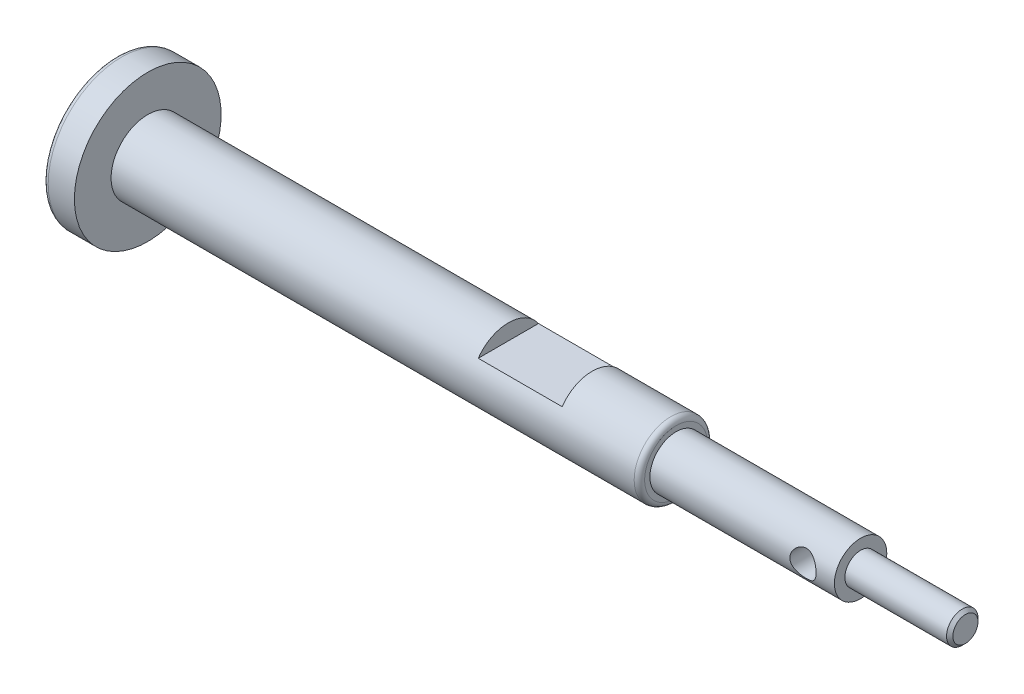
SolidWorks part; units mm, degrees
ref_plane "前视基准面" through (0, 0, 0) normal (0, 0, 1) x (1, 0, 0)
ref_plane "上视基准面" through (0, 0, 0) normal (0, 1, 0) x (1, 0, 0)
ref_plane "右视基准面" through (0, 0, 0) normal (1, 0, 0) x (0, 0, -1)
sketch "草图1" plane through (0, 0, 0) normal (1, 0, 0) x (0, 0, -1)
  circle A0 centre (0, 0) radius 3.5
  dimension "D1" = 7
extrude "凸台-拉伸1" add sketch "草图1" along normal blind 90
sketch "草图2" plane through (0, 0, 0) normal (-1, 0, 0) x (0, 0, 1)
  circle A0 centre (0, 0) radius 7
  dimension "D1" = 14
extrude "凸台-拉伸2" add sketch "草图2" along normal blind 3
fillet "圆角1" radius 0.5 1 edges at (-3, 0, 7)
sketch "草图3" plane through (0, 0, 0) normal (0, 0, 1) x (1, 0, 0)
  line L0 (0, 0) -> (33.4, 0) construction
  line L1 (33.4, 0) -> (34.4, 0) construction
  line L2 (34.4, 0) -> (34.4, 3.5) construction
  line L3 (90, 3.5) -> (0, 3.5) construction
  line L5 (42.4, 2) -> (34.4, 2)
  line L6 (42.4, 2) -> (42.4, 3.5)
  line L7 (42.4, 3.5) -> (34.4, 3.5)
  line L8 (34.4, 2) -> (34.4, 3.5)
  line L9 (42.4, 2) -> (34.4, 3.5) construction
  line L10 (42.4, 3.5) -> (34.4, 2) construction
  point P4 (38.4, 2.75)
  dimension "D1" = 33.4
  dimension "D2" = 1
  dimension "D3" = 1.5
  dimension "D4" = 8
extrude "切除-拉伸1" cut sketch "草图3" against normal through all both and the other way through all
sketch "草图4" plane through (0, 0, 0) normal (0, 0, 1) x (1, 0, 0)
  line L0 (34.4, 0) -> (50.4, 0) construction
  line L1 (50.4, 0) -> (50.4, 3.5) construction
  line L2 (90, 3.5) -> (42.4, 3.5) construction
  line L3 (90, -3.5) -> (90, 3.5) construction
  line L4 (90, 2.5) -> (50.4, 2.5)
  line L5 (90, 2.5) -> (90, 3.5)
  line L6 (90, 3.5) -> (50.4, 3.5)
  line L7 (50.4, 2.5) -> (50.4, 3.5)
  line L8 (90, 2.5) -> (50.4, 3.5) construction
  line L9 (90, 3.5) -> (50.4, 2.5) construction
  line L10 (90, -3.5) -> (50.4, -2.5) construction
  line L11 (90, -2.5) -> (50.4, -3.5) construction
  line L12 (50.4, -2.5) -> (50.4, -3.5) construction
  line L13 (90, -3.5) -> (50.4, -3.5) construction
  line L14 (90, -2.5) -> (90, -3.5) construction
  line L15 (90, -2.5) -> (50.4, -2.5) construction
  point P4 (70.2, 3)
  point P17 (70.2, -3)
  dimension "D1" = 16
  dimension "D2" = 5
revolve "切除-旋转1" cut sketch "草图4" angle 360 about L0
fillet "圆角2" radius 0.5 1 edges at (50.4, 0, 3.5)
sketch "草图5" plane through (90, 0, 0) normal (1, 0, 0) x (0, 0, -1)
  circle A0 centre (0, 0) radius 1.5
  circle A1 centre (0, 0) radius 2.5
  dimension "D1" = 3
extrude "切除-拉伸2" cut sketch "草图5" against normal blind 22
sketch "草图6" plane through (0, 0, 0) normal (0, 0, 1) x (1, 0, 0)
  line L0 (68, -2.5) -> (68, 2.5) construction
  circle A0 centre (65, 0) radius 1.25
  dimension "D2" = 2.5
  dimension "D1" = 3
extrude "切除-拉伸3" cut sketch "草图6" against normal through all both and the other way through all
sketch "草图7" plane through (90, 0, 0) normal (1, 0, 0) x (0, 0, -1)
  circle A0 centre (0, 0) radius 4.0591
extrude "切除-拉伸4" cut sketch "草图7" against normal blind 12
chamfer "倒角1" distance 0.3 angle 45 1 edges at (78, 0, -1.5)
